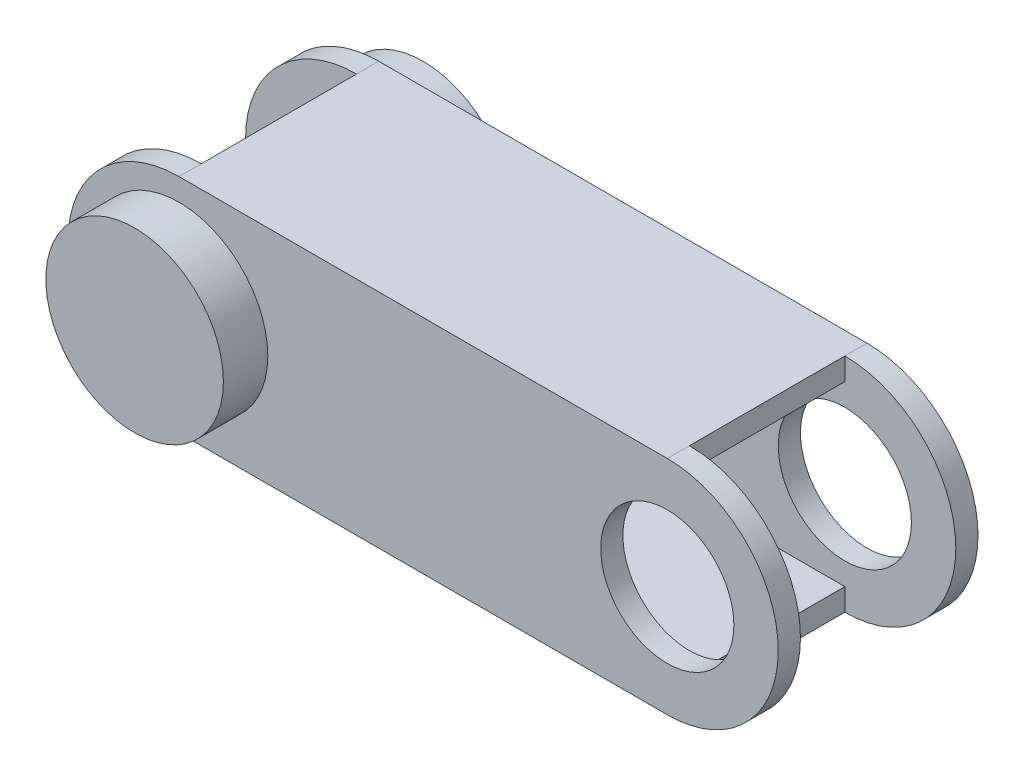
SolidWorks part; units mm, degrees
ref_plane "Front Plane" through (0, 0, 0) normal (0, 0, 1) x (1, 0, 0)
ref_plane "Top Plane" through (0, 0, 0) normal (0, 1, 0) x (1, 0, 0)
ref_plane "Right Plane" through (0, 0, 0) normal (1, 0, 0) x (0, 0, -1)
sketch "Sketch1" plane through (0, 0, 0) normal (0, 0, 1) x (1, 0, 0)
  line L0 (0, 0) -> (-220, 0) construction
  line L1 (0, -50) -> (-220, -50)
  line L2 (0, 50) -> (-220, 50)
  arc A0 (0, -50) -> (0, 50) centre (0, 0) ccw
  arc A1 (-220, 50) -> (-220, -50) centre (-220, 0) ccw
  circle A3 centre (0, 0) radius 30
  point P3 (-110, 0)
  dimension "D2" = 50
  dimension "D3" = 60
  dimension "D1" = 220
extrude "Boss-Extrude2" add sketch "Sketch1" along normal blind 10
sketch "Sketch3" plane through (0, -50, 0) normal (0, -1, 0) x (1, 0, 0)
  line L1 (0, 0) -> (-220, 0)
  line L2 (0, 0) -> (0, -80)
  line L3 (0, -80) -> (-220, -80)
  line L4 (-220, 0) -> (-220, -80)
  dimension "D1" = 80
extrude "Boss-Extrude3" add sketch "Sketch3" against normal blind 10
ref_plane "Plane1" through (0, 0, -35) normal (0, 0, -1) x (-1, 0, 0)
sketch "Sketch4" plane through (0, 0, 0) normal (0, 0, 1) x (1, 0, 0)
  circle A0 centre (-220, 0) radius 40
  dimension "D1" = 80
extrude "Boss-Extrude4" add sketch "Sketch4" along normal blind 30
mirror "Mirror1" about plane through (0, 0, -35) normal (0, 0, -1) of "Boss-Extrude3", "Boss-Extrude2", "Boss-Extrude4"
mirror "Mirror2" about plane through (0, 0, 0) normal (0, 1, 0) of "Boss-Extrude3"
